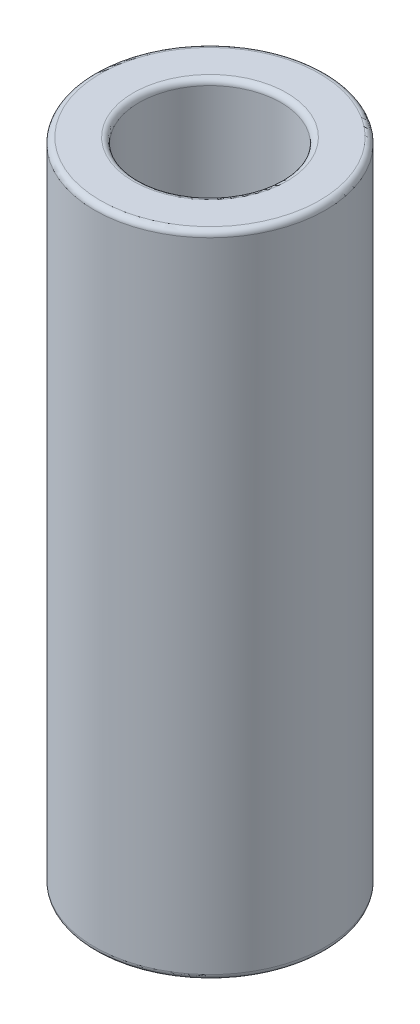
SolidWorks part; units mm, degrees
ref_plane "Front Plane" through (0, 0, 0) normal (0, 0, 1) x (1, 0, 0)
ref_plane "Top Plane" through (0, 0, 0) normal (0, 1, 0) x (1, 0, 0)
ref_plane "Right Plane" through (0, 0, 0) normal (1, 0, 0) x (0, 0, -1)
sketch "Sketch1" plane through (0, 0, 0) normal (0, 0, 1) x (1, 0, 0)
  line L0 (0, -7.962) -> (0, 7.962) construction
  line L6 (2.5, 11.43) -> (4.0625, 11.43)
  line L7 (2.5, 11.43) -> (2.5, -11.43)
  line L8 (2.5, -11.43) -> (4.0625, -11.43)
  line L9 (4.0625, 11.43) -> (4.0625, -11.43)
  point P4 (0, 0)
  point P10 (2.5, 0)
  dimension "D1" = 5
  dimension "D2" = 22.86
  dimension "D3" = 8.125
revolve "Revolve1" add sketch "Sketch1" angle 360 about L0
fillet "Fillet1" radius 0.2 4 edges at (0, -11.43, -2.5) (0, -11.43, -4.0625) (0, 11.43, -4.0625) (0, 11.43, -2.5)
